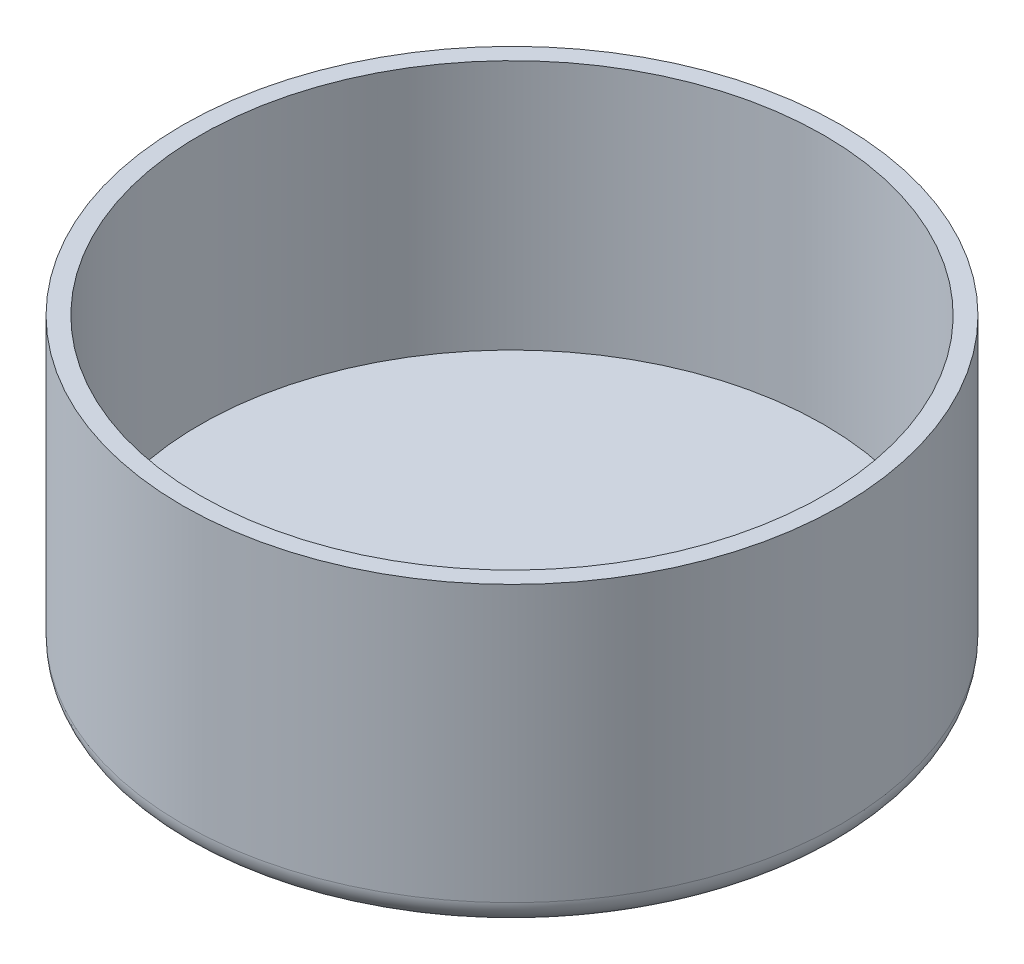
SolidWorks part; units mm, degrees
ref_plane "Front" through (0, 0, 0) normal (0, 0, 1) x (1, 0, 0)
ref_plane "Top" through (0, 0, 0) normal (0, 1, 0) x (1, 0, 0)
ref_plane "Right" through (0, 0, 0) normal (1, 0, 0) x (0, 0, -1)
sketch "Sketch1" plane through (0, 0, 0) normal (0, 1, 0) x (1, 0, 0)
  circle A0 centre (0, 0) radius 13.15
  dimension "D1" = 26.3
extrude "Boss-Extrude1" add sketch "Sketch1" along normal blind 2
sketch "Sketch2" plane through (0, 2, 0) normal (0, 1, 0) x (1, 0, 0)
  circle A0 centre (0, 0) radius 13.15 construction
  circle A1 centre (0, 0) radius 13.15
  circle A2 centre (0, 0) radius 12.45
  dimension "D1" = 0.7
extrude "Boss-Extrude2" add sketch "Sketch2" along normal blind 10
fillet "Fillet1" radius 1 1 edges at (0, 0, 13.15)
